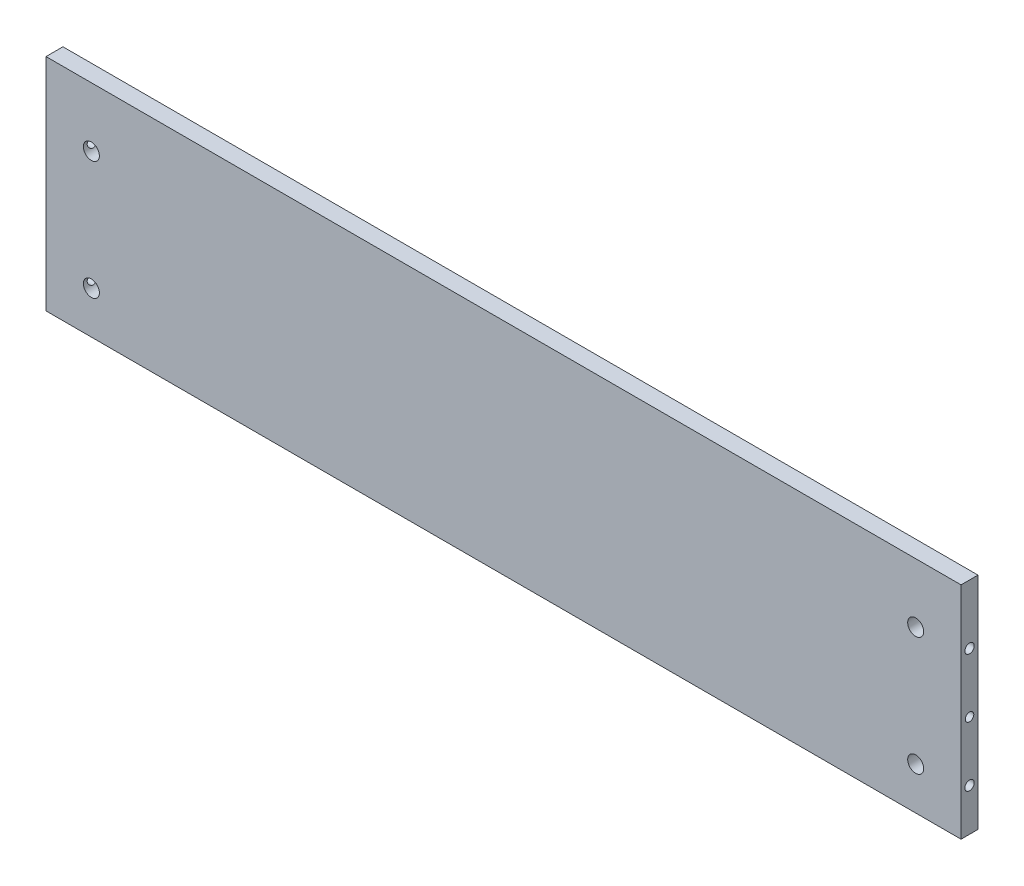
SolidWorks part; units mm, degrees
ref_plane "Front Plane" through (0, 0, 0) normal (0, 0, 1) x (1, 0, 0)
ref_plane "Top Plane" through (0, 0, 0) normal (0, 1, 0) x (1, 0, 0)
ref_plane "Right Plane" through (0, 0, 0) normal (1, 0, 0) x (0, 0, -1)
sketch "Sketch1" plane through (0, 0, 0) normal (0, 0, 1) x (1, 0, 0)
  line L1 (-342.9, -82.55) -> (342.9, -82.55)
  line L2 (-342.9, -82.55) -> (-342.9, 82.55)
  line L3 (-342.9, 82.55) -> (342.9, 82.55)
  line L4 (342.9, -82.55) -> (342.9, 82.55)
  line L5 (-342.9, -82.55) -> (342.9, 82.55) construction
  line L6 (-342.9, 82.55) -> (342.9, -82.55) construction
  point P0 (0, 0)
  dimension "D1" = 165.1
  dimension "D2" = 685.8
extrude "Boss-Extrude1" add sketch "Sketch1" along normal blind 12.7
sketch "Sketch2" plane through (342.9, 0, 0) normal (1, 0, 0) x (0, 0, -1)
  line L0 (-12.7, -82.55) -> (0, -82.55) construction
  line L6 (-6.35, -82.55) -> (-6.35, 82.55) construction
  line L7 (-12.7, 82.55) -> (0, 82.55) construction
  line L8 (-6.35, -6.35) -> (-12.7, -6.35) construction
  line L9 (-12.7, -82.55) -> (-12.7, 82.55) construction
  circle A0 centre (-6.35, -6.35) radius 3.175
  point P0 (-6.35, -82.55)
  dimension "D1" = 76.2
  dimension "D3" = 6.35
  dimension "D2" = 6.35
extrude "Cut-Extrude1" cut sketch "Sketch2" against normal blind 26.67
sketch "Sketch3" plane through (342.9, 0, 0) normal (1, 0, 0) x (0, 0, -1)
  line L0 (-6.35, -6.35) -> (-6.35, 82.55) construction
  line L2 (-12.7, 82.55) -> (0, 82.55) construction
  line L5 (-6.35, -6.35) -> (0, -6.35) construction
  line L6 (0, -82.55) -> (0, 82.55) construction
  circle A0 centre (-6.35, 38.1) radius 3.5
  circle A1 centre (-6.35, -50.8) radius 3.5
  dimension "D1" = 44.45
  dimension "D2" = 7
extrude "Cut-Extrude2" cut sketch "Sketch3" against normal blind 34
mirror "Mirror2" about plane through (0, 0, 0) normal (1, 0, 0) of "Cut-Extrude1", "Cut-Extrude2"
sketch "Sketch4" plane through (0, 0, 12.7) normal (0, 0, 1) x (1, 0, 0)
  line L0 (-342.9, -6.35) -> (342.9, -6.35) construction
  line L1 (342.9, 82.55) -> (-342.9, 82.55) construction
  line L2 (0, 82.55) -> (0, -82.55) construction
  line L4 (-342.9, 82.55) -> (-342.9, -82.55) construction
  line L5 (-342.9, -82.55) -> (342.9, -82.55) construction
  line L6 (342.9, -82.55) -> (342.9, 82.55) construction
  circle A0 centre (-308.9, 38.1) radius 6
  circle A1 centre (308.9, -50.8) radius 6
  circle A2 centre (-308.9, -50.8) radius 6
  circle A3 centre (308.9, 38.1) radius 6
  dimension "D2" = 12
  dimension "D1" = 76.2
  dimension "D3" = 44.45
  dimension "D4" = 34
extrude "Cut-Extrude3" cut sketch "Sketch4" against normal blind 9.85
sketch "Sketch5" plane through (0, -82.55, 0) normal (0, -1, 0) x (1, 0, 0)
  line L0 (-342.9, 6.35) -> (342.9, 6.35) construction
  line L1 (-342.9, 12.7) -> (-342.9, 0) construction
  line L2 (342.9, 12.7) -> (342.9, 0) construction
  line L3 (0, 12.7) -> (0, 0) construction
  line L4 (-342.9, 12.7) -> (342.9, 12.7) construction
  circle A0 centre (-209.55, 6.35) radius 1.7526
  circle A1 centre (-69.85, 6.35) radius 1.7526
  circle A2 centre (69.85, 6.35) radius 1.7526
  circle A3 centre (209.55, 6.35) radius 1.7526
  dimension "D2" = 3.5052
  dimension "D1" = 133.35
  dimension "D3" = 4
extrude "Cut-Extrude4" cut sketch "Sketch5" against normal blind 19.05
sketch "Sketch7" plane through (0, 0, 0) normal (0, 0, -1) x (-1, 0, 0)
  line L0 (201.93, 82.55) -> (201.93, -82.55) construction
  line L1 (-342.9, 82.55) -> (342.9, 82.55) construction
  line L2 (342.9, -82.55) -> (-342.9, -82.55) construction
  line L3 (342.9, 82.55) -> (342.9, -82.55) construction
  line L4 (308.9, -50.8) -> (201.93, -50.8) construction
  line L5 (255.415, -50.8) -> (255.415, -82.55) construction
  line L6 (0, -82.55) -> (0, 82.55) construction
  circle A0 centre (278.4337, -61.9125) radius 1.7526
  circle A1 centre (232.3962, -61.9125) radius 1.7526
  circle A2 centre (-232.3962, -61.9125) radius 1.7526
  circle A3 centre (-278.4337, -61.9125) radius 1.7526
  dimension "D2" = 3.5052
  dimension "D1" = 140.97
  dimension "D3" = 20.6375
  dimension "D4" = 23.0188
extrude "Cut-Extrude5" cut sketch "Sketch7" against normal blind 11.43
